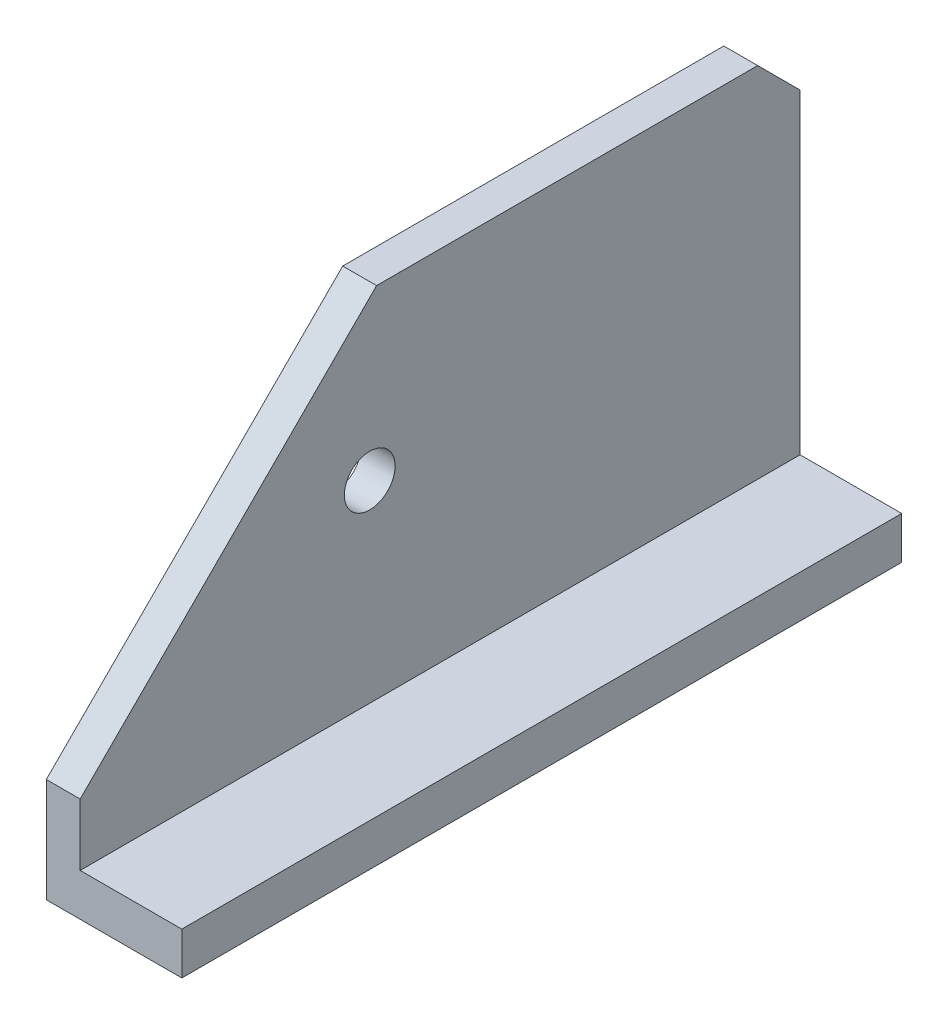
SolidWorks part; units mm, degrees
ref_plane "Спереди" through (0, 0, 0) normal (0, 0, 1) x (1, 0, 0)
ref_plane "Сверху" through (0, 0, 0) normal (0, 1, 0) x (1, 0, 0)
ref_plane "Справа" through (0, 0, 0) normal (1, 0, 0) x (0, 0, -1)
sketch "Эскиз1" plane through (0, 0, 0) normal (0, 0, 1) x (1, 0, 0)
  line L1 (0, 0) -> (12, 0)
  line L3 (-4, -5) -> (12, -5)
  line L4 (12, 0) -> (12, -5)
  line L6 (0, 0) -> (0, 42.3)
  line L7 (0, 42.3) -> (-4, 42.3)
  line L8 (-4, -5) -> (-4, 42.3)
extrude "Вытянуть1" add sketch "Эскиз1" along normal blind 85
sketch "Эскиз2" plane through (-4, 0, 0) normal (-1, 0, 0) x (0, 0, 1)
  circle A0 centre (50.8135, 22.7734) radius 3
extrude "Вырез-Вытянуть1" cut sketch "Эскиз2" against normal through all
chamfer "Фаска1" distance 35 angle 45 1 edges at (-2, 42.3, 85)
chamfer "Фаска2" distance 5 angle 45 1 edges at (-2, 42.3, 0)
